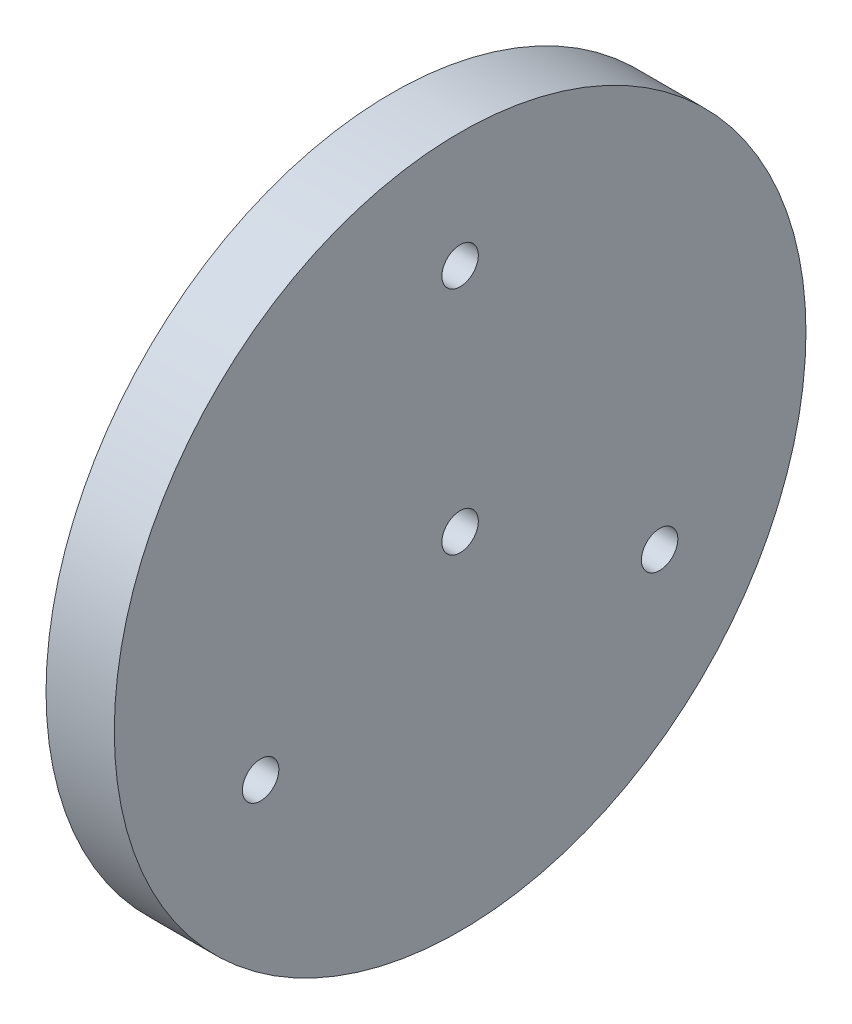
SolidWorks part; units mm, degrees
material "Beech"
ref_plane "Ebene vorne" through (0, 0, 0) normal (0, 0, 1) x (1, 0, 0)
ref_plane "Ebene oben" through (0, 0, 0) normal (0, 1, 0) x (1, 0, 0)
ref_plane "Ebene rechts" through (0, 0, 0) normal (1, 0, 0) x (0, 0, -1)
sketch "Sketch1" plane through (0, 0, 0) normal (1, 0, 0) x (0, 0, -1)
  line L0 (0, 76) -> (0, -76) construction
  circle A0 centre (0, 0) radius 76
  circle A1 centre (0, 0) radius 4
  circle A2 centre (0, 50.6196) radius 4
  circle A3 centre (43.8378, -25.3098) radius 4
  circle A4 centre (-43.8378, -25.3098) radius 4
  point P14 (0, 0)
  dimension "D1" = 152
  dimension "D2" = 8
  dimension "D3" = 8
  dimension "D4" = 3
extrude "Boss-Extrude1" add sketch "Sketch1" along normal blind 15
